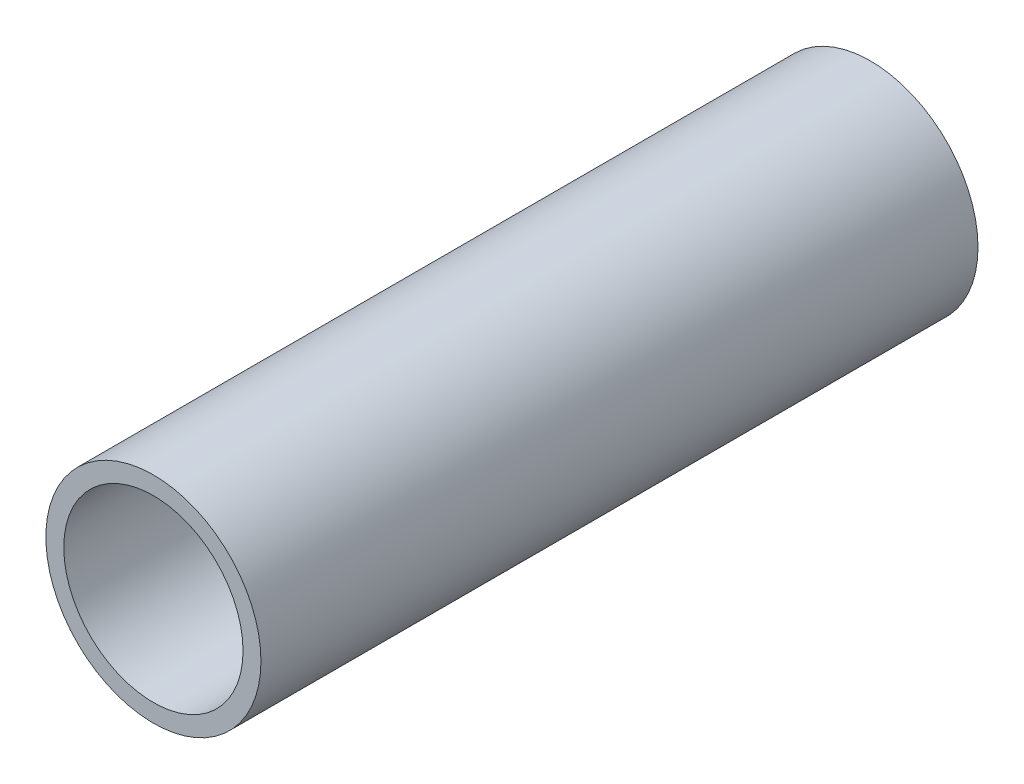
SolidWorks part; units mm, degrees
ref_plane "Front Plane" through (0, 0, 0) normal (0, 0, 1) x (1, 0, 0)
ref_plane "Top Plane" through (0, 0, 0) normal (0, 1, 0) x (1, 0, 0)
ref_plane "Right Plane" through (0, 0, 0) normal (1, 0, 0) x (0, 0, -1)
sketch "Sketch1" plane through (0, 0, 0) normal (0, 0, 1) x (1, 0, 0)
  circle A0 centre (0, 0) radius 30
  circle A1 centre (0, 0) radius 25
  dimension "D1" = 60
  dimension "D2" = 50
extrude "Boss-Extrude1" add sketch "Sketch1" along normal blind 200
